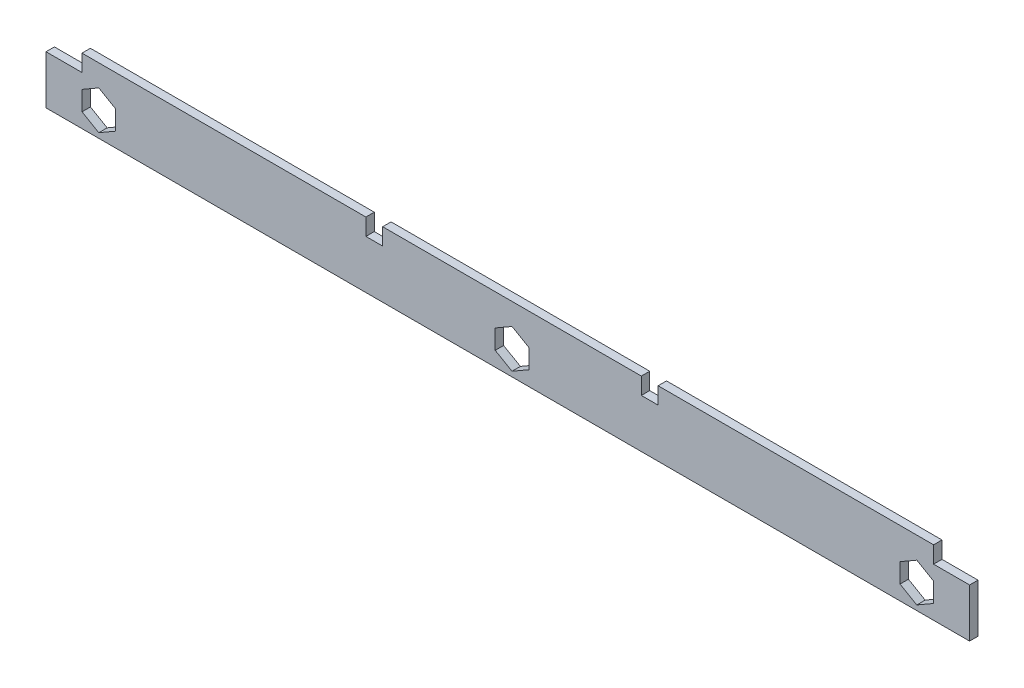
SolidWorks part; units mm, degrees
ref_plane "Front Plane" through (0, 0, 0) normal (0, 0, 1) x (1, 0, 0)
ref_plane "Top Plane" through (0, 0, 0) normal (0, 1, 0) x (1, 0, 0)
ref_plane "Right Plane" through (0, 0, 0) normal (1, 0, 0) x (0, 0, -1)
sketch "Sketch1" plane through (0, 0, 0) normal (0, 0, 1) x (1, 0, 0)
  line L0 (6607.5347, 2635.322) -> (6607.5347, 2638.497)
  line L1 (6446.5241, 2635.322) -> (6446.5241, 2638.497)
  line L2 (6555.452, 2635.322) -> (6555.452, 2638.497)
  line L3 (6552.277, 2635.322) -> (6552.277, 2638.497)
  line L4 (6531.0007, 2632.5577) -> (6527.8257, 2634.3908)
  line L5 (6527.8257, 2634.3908) -> (6524.6507, 2632.5577)
  line L6 (6524.6507, 2632.5577) -> (6524.6507, 2628.8915)
  line L7 (6524.6507, 2628.8915) -> (6527.8257, 2627.0584)
  line L8 (6527.8257, 2627.0584) -> (6531.0007, 2628.8915)
  line L9 (6531.0007, 2628.8915) -> (6531.0007, 2632.5577)
  line L10 (6614.3419, 2635.322) -> (6607.5347, 2635.322)
  line L11 (6555.452, 2635.322) -> (6552.277, 2635.322)
  line L12 (6503.3744, 2635.322) -> (6500.1994, 2635.322)
  line L13 (6446.5241, 2635.322) -> (6439.7169, 2635.322)
  line L14 (6607.5347, 2638.497) -> (6555.452, 2638.497)
  line L15 (6552.277, 2638.497) -> (6503.3744, 2638.497)
  line L16 (6500.1994, 2638.497) -> (6446.5241, 2638.497)
  line L17 (6614.3419, 2626.1272) -> (6439.7169, 2626.1272)
  line L18 (6503.3744, 2638.497) -> (6503.3744, 2635.322)
  line L19 (6500.1994, 2638.497) -> (6500.1994, 2635.322)
  line L20 (6452.8741, 2632.5577) -> (6449.6991, 2634.3908)
  line L21 (6449.6991, 2634.3908) -> (6446.5241, 2632.5577)
  line L22 (6446.5241, 2632.5577) -> (6446.5241, 2628.8915)
  line L23 (6446.5241, 2628.8915) -> (6449.6991, 2627.0584)
  line L24 (6449.6991, 2627.0584) -> (6452.8741, 2628.8915)
  line L25 (6452.8741, 2628.8915) -> (6452.8741, 2632.5577)
  line L26 (6607.5347, 2632.5577) -> (6604.3597, 2634.3908)
  line L27 (6604.3597, 2634.3908) -> (6601.1847, 2632.5577)
  line L28 (6601.1847, 2632.5577) -> (6601.1847, 2628.8915)
  line L29 (6601.1847, 2628.8915) -> (6604.3597, 2627.0584)
  line L30 (6604.3597, 2627.0584) -> (6607.5347, 2628.8915)
  line L31 (6607.5347, 2628.8915) -> (6607.5347, 2632.5577)
  line L32 (6439.7169, 2626.1272) -> (6439.7169, 2635.322)
  line L33 (6614.3419, 2626.1272) -> (6614.3419, 2635.322)
extrude "Boss-Extrude1" add sketch "Sketch1" along normal blind 1.5875
